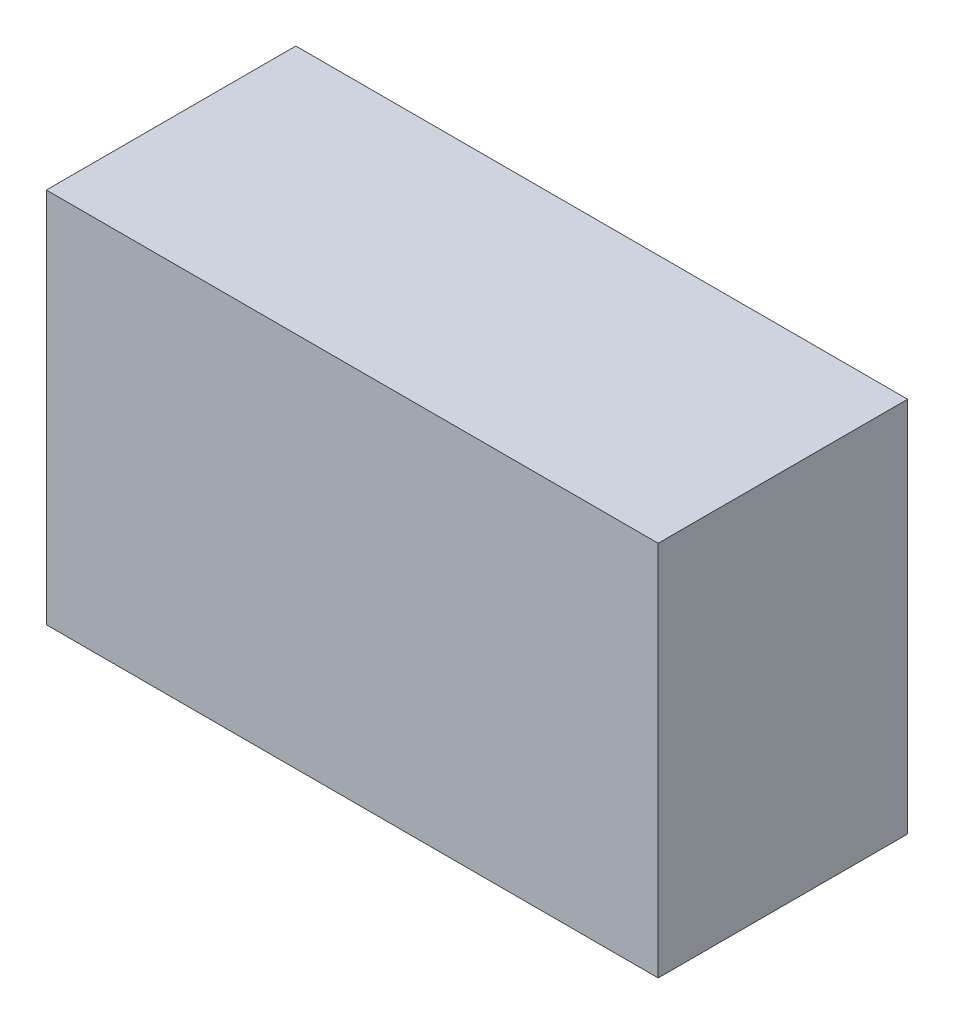
SolidWorks part; units mm, degrees
material "Plastique personnalisé"
ref_plane "Plan de face" through (0, 0, 0) normal (0, 0, 1) x (1, 0, 0)
ref_plane "Plan de dessus" through (0, 0, 0) normal (0, 1, 0) x (1, 0, 0)
ref_plane "Plan de droite" through (0, 0, 0) normal (1, 0, 0) x (0, 0, -1)
sketch "Esquisse1" plane through (0, 0, 0) normal (0, 1, 0) x (1, 0, 0)
  line L1 (-23.6607, 12.4554) -> (41.3393, 12.4554)
  line L2 (-23.6607, 12.4554) -> (-23.6607, -14.0446)
  line L3 (-23.6607, -14.0446) -> (41.3393, -14.0446)
  line L4 (41.3393, 12.4554) -> (41.3393, -14.0446)
  dimension "D1" = 65
  dimension "D2" = 26.5
extrude "Boss.-Extru.1" add sketch "Esquisse1" along normal blind 40 contours L1 L4 L3 L2
ref_plane "Plan1" through (0, 0, -12.4554) normal (0, 0, -1) x (-1, 0, 0)
